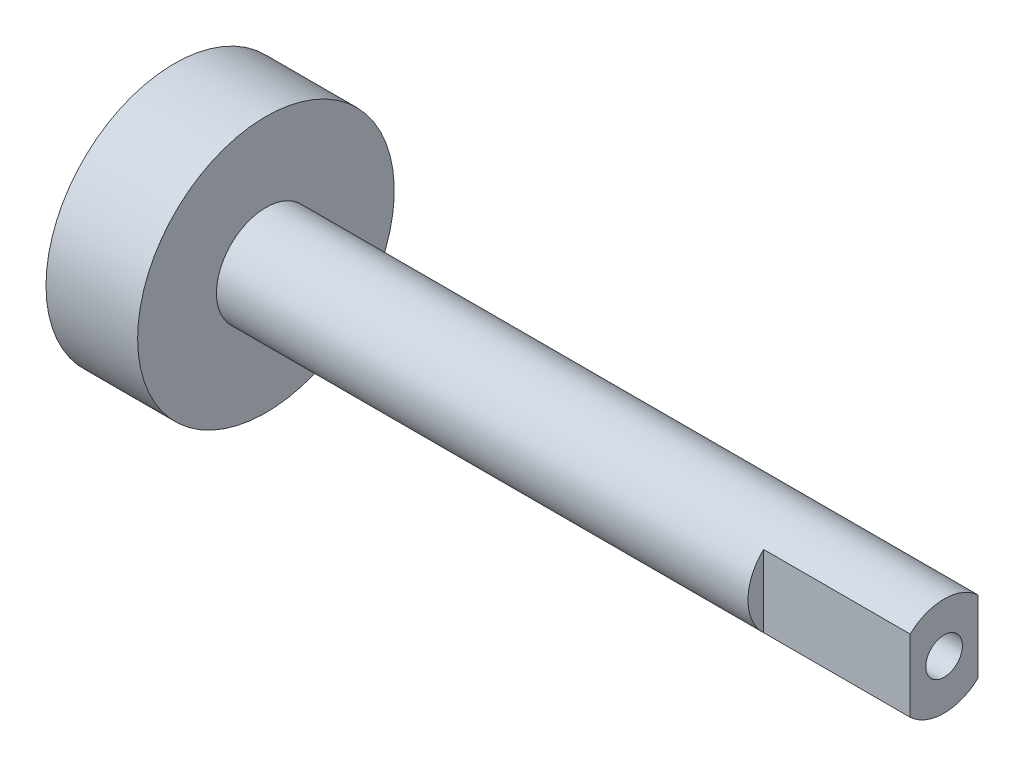
SolidWorks part; units mm, degrees
ref_plane "Front Plane" through (0, 0, 0) normal (0, 0, 1) x (1, 0, 0)
ref_plane "Top Plane" through (0, 0, 0) normal (0, 1, 0) x (1, 0, 0)
ref_plane "Right Plane" through (0, 0, 0) normal (1, 0, 0) x (0, 0, -1)
sketch "Sketch1" plane through (0, 0, 0) normal (1, 0, 0) x (0, 0, -1)
  circle A0 centre (0, 0) radius 2.7
  dimension "D1" = 5.4
extrude "Boss-Extrude1" add sketch "Sketch1" along normal mid plane 37
sketch "Sketch2" plane through (18.5, 0, 0) normal (1, 0, 0) x (0, 0, -1)
  line L0 (-1.85, 1.9666) -> (-1.85, -1.9666)
  line L1 (1.85, 1.9666) -> (1.85, -1.9666)
  arc A0 (-1.85, 1.9666) -> (-1.85, -1.9666) centre (0, 0) ccw
  arc A1 (1.85, -1.9666) -> (1.85, 1.9666) centre (0, 0) ccw
  dimension "D3" = 5.4
  dimension "D1" = 3.7
  dimension "D2" = 1.85
extrude "Cut-Extrude1" cut sketch "Sketch2" against normal blind 8
sketch "Sketch3" plane through (18.5, 0, 0) normal (1, 0, 0) x (0, 0, -1)
  circle A0 centre (0, 0) radius 1
  dimension "D1" = 2
extrude "Cut-Extrude2" cut sketch "Sketch3" against normal blind 6
ref_plane "Plane1" through (-18.5, 0, 0) normal (-1, 0, 0) x (0, 0, 1)
sketch "Sketch5" plane through (-18.5, 0, 0) normal (-1, 0, 0) x (0, 0, 1)
  circle A0 centre (0, 0) radius 7
  dimension "D1" = 14
extrude "Boss-Extrude2" add sketch "Sketch5" along normal blind 5 contours A0
